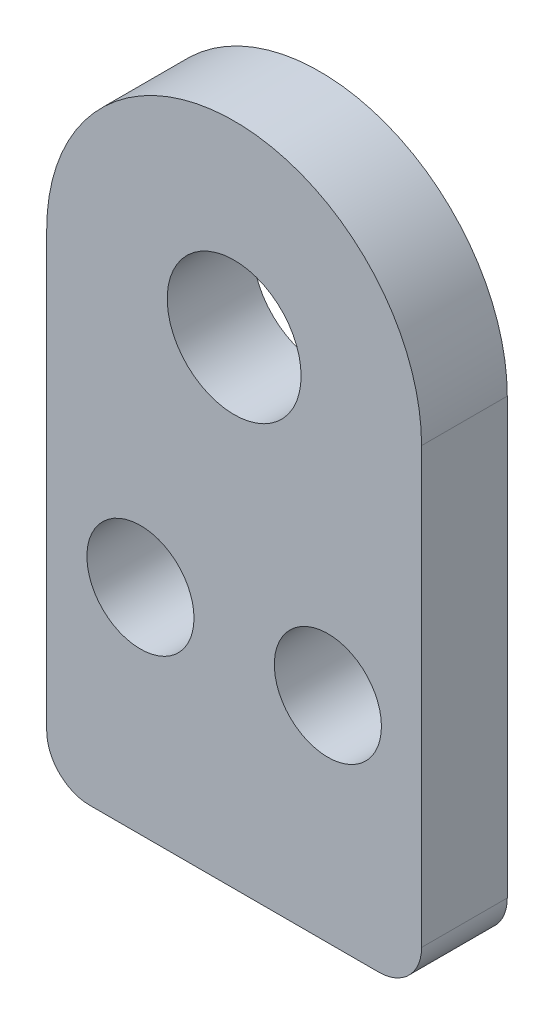
SolidWorks part; units mm, degrees
ref_plane "Front Plane" through (0, 0, 0) normal (0, 0, 1) x (1, 0, 0)
ref_plane "Top Plane" through (0, 0, 0) normal (0, 1, 0) x (1, 0, 0)
ref_plane "Right Plane" through (0, 0, 0) normal (1, 0, 0) x (0, 0, -1)
sketch "Sketch1" plane through (0, 0, 0) normal (0, 0, 1) x (1, 0, 0)
  line L0 (-11.1125, 15.6083) -> (-11.1125, 12.7)
  line L1 (-11.1125, -12.7) -> (11.1125, -12.7)
  line L2 (-11.1125, -12.7) -> (-11.1125, 12.7)
  line L3 (-11.1125, 12.7) -> (11.1125, 12.7) construction
  line L4 (11.1125, -12.7) -> (11.1125, 12.7)
  line L5 (-11.1125, -12.7) -> (11.1125, 12.7) construction
  line L6 (-11.1125, 12.7) -> (11.1125, -12.7) construction
  line L7 (-11.1125, 0) -> (0, 0) construction
  line L8 (0, 0) -> (11.1125, 0) construction
  line L9 (11.1125, 15.6083) -> (11.1125, 12.7)
  circle A0 centre (0, 15.6083) radius 3.9688
  circle A1 centre (-5.5563, 0) radius 3.175
  circle A2 centre (5.5563, 0) radius 3.175
  circle A3 centre (0, 15.6083) radius 11.1125 construction
  arc A4 (-11.1125, 15.6083) -> (11.1125, 15.6083) centre (0, 15.6083) cw
  point P0 (0, 0)
  dimension "D2" = 7.9375
  dimension "D4" = 6.35
  dimension "D3" = 11.1125
  dimension "D1" = 25.4
  dimension "D5" = 2.9083
extrude "Boss-Extrude1" add sketch "Sketch1" along normal blind 5.08
fillet "Fillet1" radius 2.54 2 edges at (-11.1125, -12.7, 2.54) (11.1125, -12.7, 2.54)
